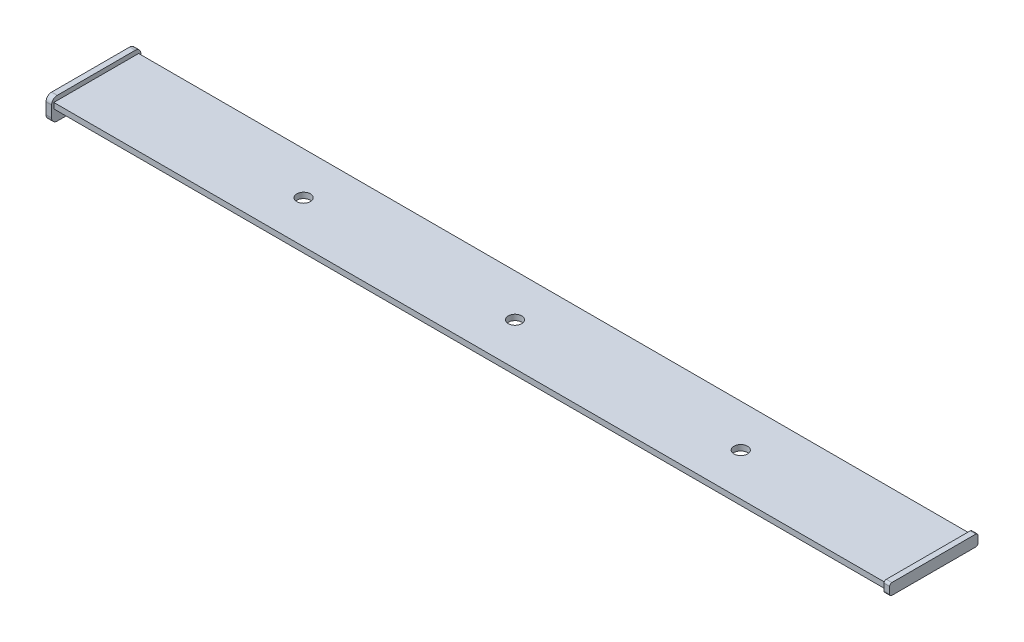
SolidWorks part; units mm, degrees
material "5052-O"
ref_plane "Front Plane" through (0, 0, 0) normal (0, 0, 1) x (1, 0, 0)
ref_plane "Top Plane" through (0, 0, 0) normal (0, 1, 0) x (1, 0, 0)
ref_plane "Right Plane" through (0, 0, 0) normal (1, 0, 0) x (0, 0, -1)
sketch "Sketch1" plane through (0, 0, 0) normal (0, 1, 0) x (1, 0, 0)
  line L1 (-1875, -189.8438) -> (1875, -189.8438)
  line L2 (-1875, -189.8438) -> (-1875, 189.8438)
  line L3 (-1875, 189.8438) -> (1875, 189.8438)
  line L4 (1875, -189.8438) -> (1875, 189.8438)
  line L5 (-1875, -189.8438) -> (1875, 189.8438) construction
  line L6 (-1875, 189.8438) -> (1875, -189.8438) construction
  point P0 (0, 0)
  dimension "D1" = 3750
extrude "Boss-Extrude1" add sketch "Sketch1" along normal blind 25
sketch "Sketch2" plane through (0, 0, 0) normal (0, -1, 0) x (1, 0, 0)
  line L0 (-1875, -189.8438) -> (-1875, 189.8438) construction
  line L1 (1931.1462, 157.6118) -> (-1875, 157.6118)
  line L2 (1931.1462, 157.6118) -> (1931.1462, 142.6118)
  line L3 (1931.1462, 142.6118) -> (-1875, 142.6118)
  line L4 (-1875, 157.6118) -> (-1875, 142.6118)
  line L5 (1931.1462, 157.6118) -> (-1875, 142.6118) construction
  line L6 (1931.1462, 142.6118) -> (-1875, 157.6118) construction
  line L7 (34.375, 0) -> (-34.375, 0) construction
  line L8 (1931.1462, -157.6118) -> (1931.1462, -142.6118)
  line L9 (-1875, -157.6118) -> (-1875, -142.6118)
  line L10 (1931.1462, -142.6118) -> (-1875, -142.6118)
  line L11 (1931.1462, -157.6118) -> (-1875, -157.6118)
  point P0 (28.0731, 150.1118)
  dimension "D1" = 150
  dimension "D2" = 15
extrude "Cut-Extrude1" cut sketch "Sketch2" against normal blind 15
sketch "Sketch3" plane through (0, 0, 0) normal (0, -1, 0) x (1, 0, 0)
  circle A0 centre (0, 0) radius 30.3811
  circle A1 centre (-946.3055, 0) radius 30.3811
  circle A2 centre (1010.6037, 0) radius 30.3811
extrude "Cut-Extrude2" cut sketch "Sketch3" against normal through all
sketch "Sketch4" plane through (1875, 0, 0) normal (1, 0, 0) x (0, 0, -1)
  line L0 (-142.6118, 0) -> (142.6118, 0) construction
  line L1 (-187.8144, -12.5) -> (187.8144, -12.5)
  line L2 (-197.8144, -2.5) -> (-197.8144, 27.5)
  line L3 (-187.8144, 37.5) -> (187.8144, 37.5)
  line L4 (197.8144, -2.5) -> (197.8144, 27.5)
  line L5 (-197.8144, -12.5) -> (197.8144, 37.5) construction
  line L6 (-197.8144, 37.5) -> (197.8144, -12.5) construction
  arc A0 (187.8144, -12.5) -> (197.8144, -2.5) centre (187.8144, -2.5) ccw
  arc A1 (187.8144, 37.5) -> (197.8144, 27.5) centre (187.8144, 27.5) cw
  arc A2 (-187.8144, -12.5) -> (-197.8144, -2.5) centre (-187.8144, -2.5) cw
  arc A3 (-197.8144, 27.5) -> (-187.8144, 37.5) centre (-187.8144, 27.5) cw
  point P0 (0, 12.5)
  dimension "D1" = 10
  dimension "D2" = 50
  dimension "D3" = 12.5
extrude "Boss-Extrude2" add sketch "Sketch4" against normal blind 25
sketch "Sketch5" plane through (-1875, 0, 0) normal (-1, 0, 0) x (0, 0, 1)
  line L0 (-142.6118, 0) -> (142.6118, 0) construction
  line L1 (-174.8437, 45) -> (174.8438, 45)
  line L2 (-199.8438, 20) -> (-199.8438, -30)
  line L3 (-174.8437, -55) -> (174.8437, -55)
  line L4 (199.8438, 20) -> (199.8438, -30)
  line L5 (-189.8438, 25) -> (-189.8438, 0) construction
  line L6 (189.8438, 25) -> (189.8438, 0) construction
  arc A0 (-199.8438, -30) -> (-174.8437, -55) centre (-174.8438, -30) ccw
  arc A1 (174.8437, -55) -> (199.8438, -30) centre (174.8438, -30) ccw
  arc A2 (174.8438, 45) -> (199.8438, 20) centre (174.8438, 20) cw
  arc A3 (-174.8437, 45) -> (-199.8438, 20) centre (-174.8438, 20) ccw
  point P10 (189.8438, 12.5)
  point P13 (-199.8438, -55)
  point P20 (-199.8438, 45)
  dimension "D5" = 25
  dimension "D1" = 55
  dimension "D2" = 100
  dimension "D3" = 10
  dimension "D4" = 10
extrude "Boss-Extrude3" add sketch "Sketch5" along normal blind 25
